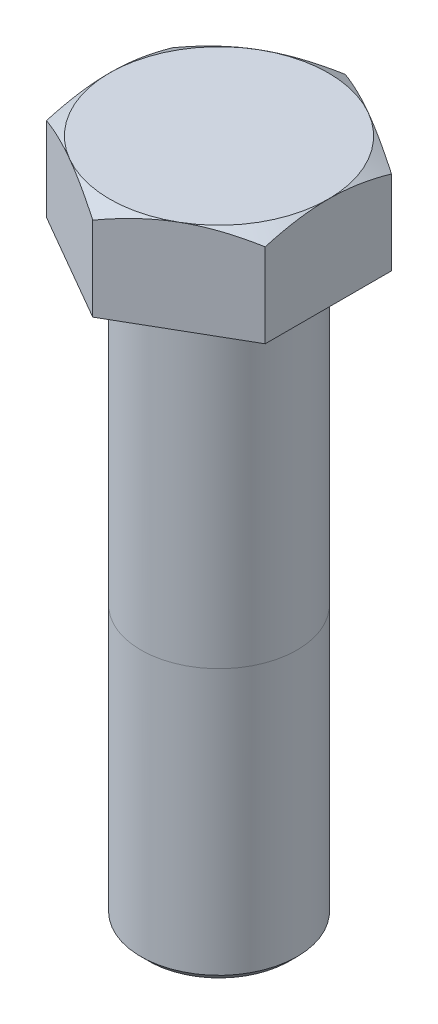
SolidWorks part; units mm, degrees
ref_plane "Front Plane" through (0, 0, 0) normal (0, 0, 1) x (1, 0, 0)
ref_plane "Top Plane" through (0, 0, 0) normal (0, 1, 0) x (1, 0, 0)
ref_plane "Right Plane" through (0, 0, 0) normal (1, 0, 0) x (0, 0, -1)
sketch "Sketch6" plane through (0, 0, 0) normal (0, 1, 0) x (1, 0, 0)
  line L1 (0, 16.1658) -> (-14, 8.0829)
  line L2 (-14, 8.0829) -> (-14, -8.0829)
  line L3 (-14, -8.0829) -> (0, -16.1658)
  line L4 (0, -16.1658) -> (14, -8.0829)
  line L5 (14, -8.0829) -> (14, 8.0829)
  line L6 (14, 8.0829) -> (0, 16.1658)
  circle A0 centre (0, 0) radius 14 construction
extrude "Boss-Extrude1" add sketch "Sketch6" along normal blind 12
sketch "Sketch7" plane through (0, 12, 0) normal (0, 1, 0) x (1, 0, 0)
  line L0 (14, 8.0829) -> (0, 16.1658) construction
  circle A0 centre (0, 0) radius 14
extrude "Cut-Extrude1" cut sketch "Sketch7" against normal blind 12 draft 60 flip side to cut
sketch "Sketch8" plane through (0, 0, 0) normal (0, -1, 0) x (1, 0, 0)
  circle A0 centre (0, 0) radius 10
extrude "Boss-Extrude2" add sketch "Sketch8" along normal blind 75
chamfer "Chamfer1" distance 1 angle 45 1 edges at (0, -75, -10)
sketch "Sketch11" plane through (0, 0, 0) normal (0, 0, 1) x (1, 0, 0)
  line L0 (-10, -40) -> (10, -40)
  line L1 (-10, 0) -> (-10, -74) construction
  line L2 (10, -74) -> (10, 0) construction
  line L3 (0, 0) -> (14, 0) construction
  point P8 (7, 0)
  dimension "D1" = 40
split line "Split Line5"
